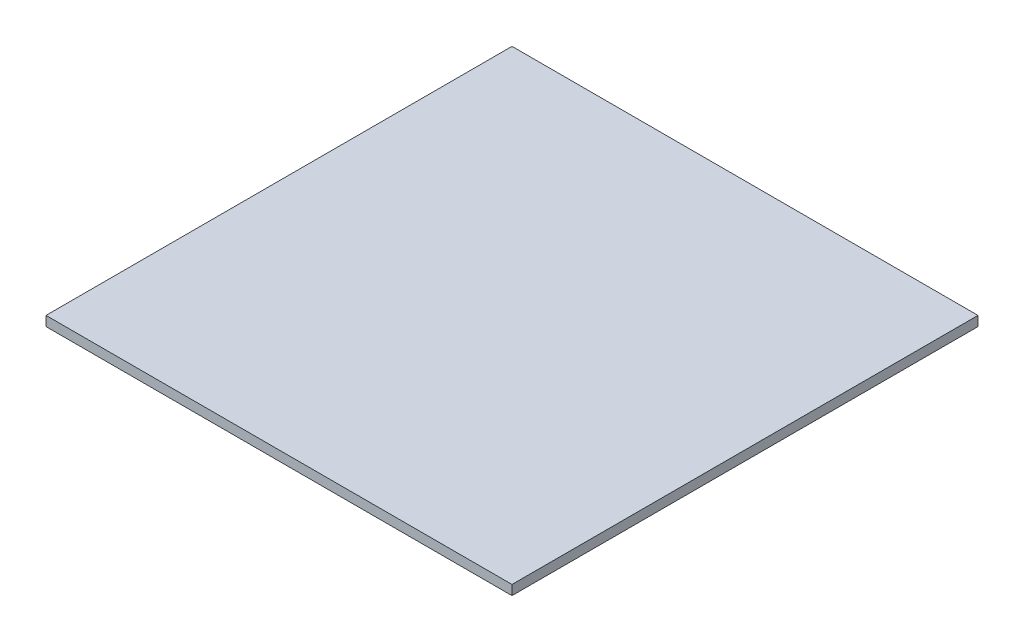
SolidWorks part; units mm, degrees
material "Beech"
ref_plane "Front Plane" through (0, 0, 0) normal (0, 0, 1) x (1, 0, 0)
ref_plane "Top Plane" through (0, 0, 0) normal (0, 1, 0) x (1, 0, 0)
ref_plane "Right Plane" through (0, 0, 0) normal (1, 0, 0) x (0, 0, -1)
sketch "Sketch1" plane through (0, 0, 0) normal (0, 1, 0) x (1, 0, 0)
  line L1 (0, 0) -> (304.8, 0)
  line L2 (0, 0) -> (0, 304.8)
  line L3 (0, 304.8) -> (304.8, 304.8)
  line L4 (304.8, 0) -> (304.8, 304.8)
  dimension "D1" = 304.8
  dimension "D2" = 304.8
extrude "Boss-Extrude1" add sketch "Sketch1" along normal blind 6.35
